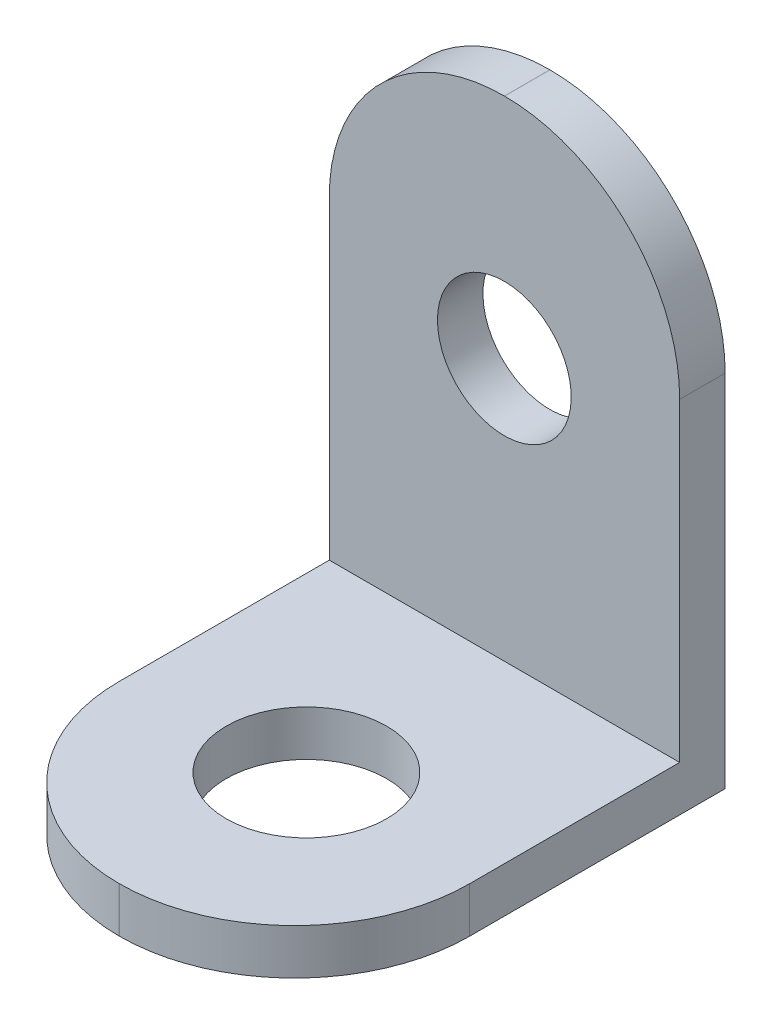
SolidWorks part; units mm, degrees
ref_plane "Front Plane" through (0, 0, 0) normal (0, 0, 1) x (1, 0, 0)
ref_plane "Top Plane" through (0, 0, 0) normal (0, 1, 0) x (1, 0, 0)
ref_plane "Right Plane" through (0, 0, 0) normal (1, 0, 0) x (0, 0, -1)
ref_plane "Plane1" through (6.654, 0, 0) normal (1, 0, 0) x (0, 0, -1)
sketch "Sketch1" plane through (6.654, 0, 0) normal (1, 0, 0) x (0, 0, -1)
  line L0 (10, 0) -> (10, 20)
  line L1 (10, 20) -> (-6.1, 20)
  line L2 (-6.1, 20) -> (-6.1, 0)
  line L3 (-6.1, 0) -> (10, 0)
extrude "Boss-Extrude1" add sketch "Sketch1" against normal blind 13.1
sketch "Sketch2" plane through (-6.446, 0, 0) normal (-1, 0, 0) x (0, 0, 1)
  line L0 (-8.3, 20) -> (-8.3, 1.7)
  line L1 (-8.3, 1.7) -> (6.1, 1.7)
  line L2 (6.1, 1.7) -> (6.1, 20)
  line L3 (6.1, 20) -> (-8.3, 20)
extrude "Cut-Extrude1" cut sketch "Sketch2" against normal through all
fillet "Fillet1" radius 6.545 4 edges at (-6.446, 0.85, 6.1) (6.654, 0.85, 6.1) (-6.446, 20, -9.15) (6.654, 20, -9.15)
sketch "Sketch20" plane through (0, 0, 0) normal (0, -1, 0) x (1, 0, 0)
  line L0 (-6.446, -10) -> (6.654, -10) construction
  circle A0 centre (0, -1) radius 3
  dimension "D1" = 9
  dimension "D2" = 6
extrude "Cut-Extrude2" cut sketch "Sketch20" against normal blind 10
sketch "Sketch21" plane through (0, 0, -10) normal (0, 0, -1) x (-1, 0, 0)
  line L0 (6.446, 0) -> (-6.654, 0) construction
  circle A0 centre (-0.099, 11.5) radius 2.5
  dimension "D1" = 5
  dimension "D2" = 11.5
extrude "Cut-Extrude3" cut sketch "Sketch21" against normal blind 10
